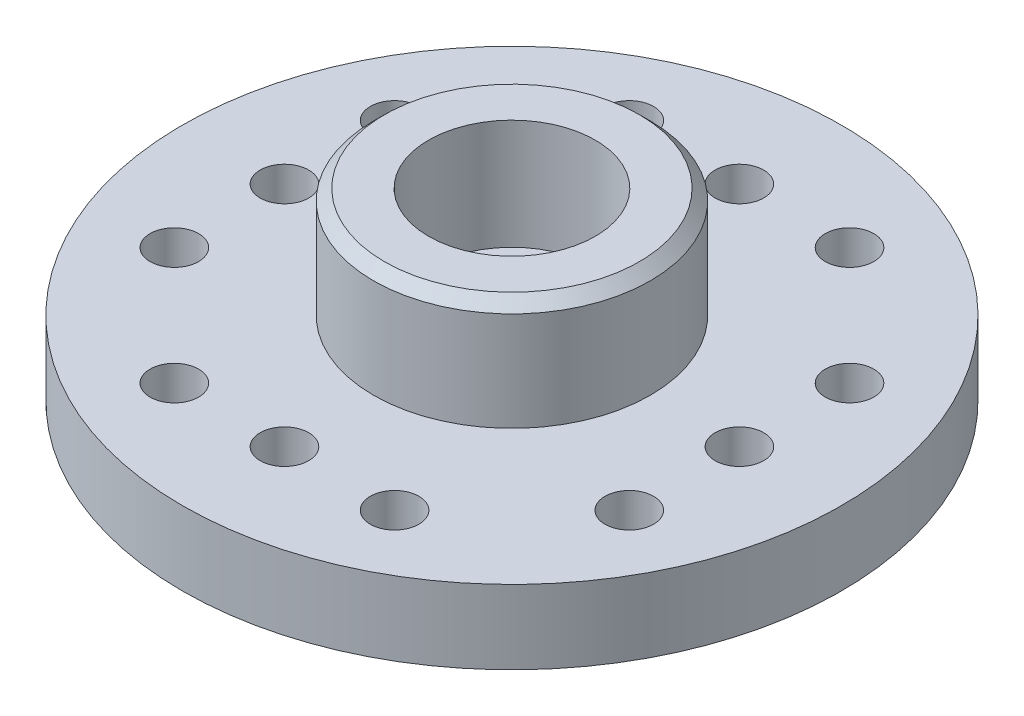
SolidWorks part; units mm, degrees
ref_plane "前视基准面" through (0, 0, 0) normal (0, 0, 1) x (1, 0, 0)
ref_plane "上视基准面" through (0, 0, 0) normal (0, 1, 0) x (1, 0, 0)
ref_plane "右视基准面" through (0, 0, 0) normal (1, 0, 0) x (0, 0, -1)
sketch "草图2" plane through (0, 0, 0) normal (0, 1, 0) x (1, 0, 0)
  line L0 (26.7509, 0) -> (-26.7509, 0) construction
  line L1 (0, 14.5485) -> (0, -14.5485) construction
  circle A0 centre (0, 0) radius 10.475
  circle A1 centre (0, 0) radius 4.4
  circle A2 centre (0, 7.23) radius 0.7717
  circle A3 centre (-3.5, 7.23) radius 0.7717
  circle A5 centre (3.5, 7.23) radius 0.7717
  circle A6 centre (7.23, 3.5) radius 0.7717
  circle A7 centre (7.23, 0) radius 0.7717
  circle A8 centre (7.23, -3.5) radius 0.7717
  circle A9 centre (3.5, -7.23) radius 0.7717
  circle A10 centre (0, -7.23) radius 0.7717
  circle A11 centre (-3.5, -7.23) radius 0.7717
  circle A12 centre (-7.23, -3.5) radius 0.7717
  circle A13 centre (-7.23, 0) radius 0.7717
  circle A14 centre (-7.23, 3.5) radius 0.7717
  point P4 (0, 0)
  point P8 (0, 0)
  point P37 (0, 0)
  dimension "D1" = 20.95
  dimension "D2" = 8.8
  dimension "D3" = 3.5
  dimension "D4" = 4
  dimension "D5" = 7.23
extrude "凸台-拉伸1" add sketch "草图2" along normal blind 2.35
sketch "草图3" plane through (0, 2.35, 0) normal (0, 1, 0) x (1, 0, 0)
  circle A0 centre (0, 0) radius 2.65
  circle A2 centre (0, 0) radius 4.4
  dimension "D1" = 5.3
extrude "凸台-拉伸2" add sketch "草图3" along normal blind 3.5 separate body
chamfer "倒角1" distance 0.35 angle 45 1 edges at (0, 5.85, 4.4)
sketch "草图4" plane through (0, 0, 0) normal (0, -1, 0) x (1, 0, 0)
  circle A2 centre (0, 0) radius 4.4
extrude "凸台-拉伸3" add sketch "草图4" against normal blind 2.35
sketch "草图5" plane through (0, 0, 0) normal (0, -1, 0) x (1, 0, 0)
  circle A0 centre (0, 0) radius 3
  dimension "D1" = 6
extrude "切除-拉伸1" cut sketch "草图5" against normal blind 1
sketch "草图6" plane through (0, 2.35, 0) normal (0, 1, 0) x (1, 0, 0)
  circle A0 centre (0, 0) radius 1.425
  dimension "D1" = 2.85
extrude "切除-拉伸2" cut sketch "草图6" against normal blind 1.35
sketch "草图7" plane through (0, 0, 0) normal (0, -1, 0) x (1, 0, 0)
  circle A0 centre (0, 0) radius 3.5
  circle A1 centre (0, 0) radius 4.325
  dimension "D1" = 8.65
  dimension "D2" = 7
extrude "切除-拉伸3" cut sketch "草图7" against normal blind 1
